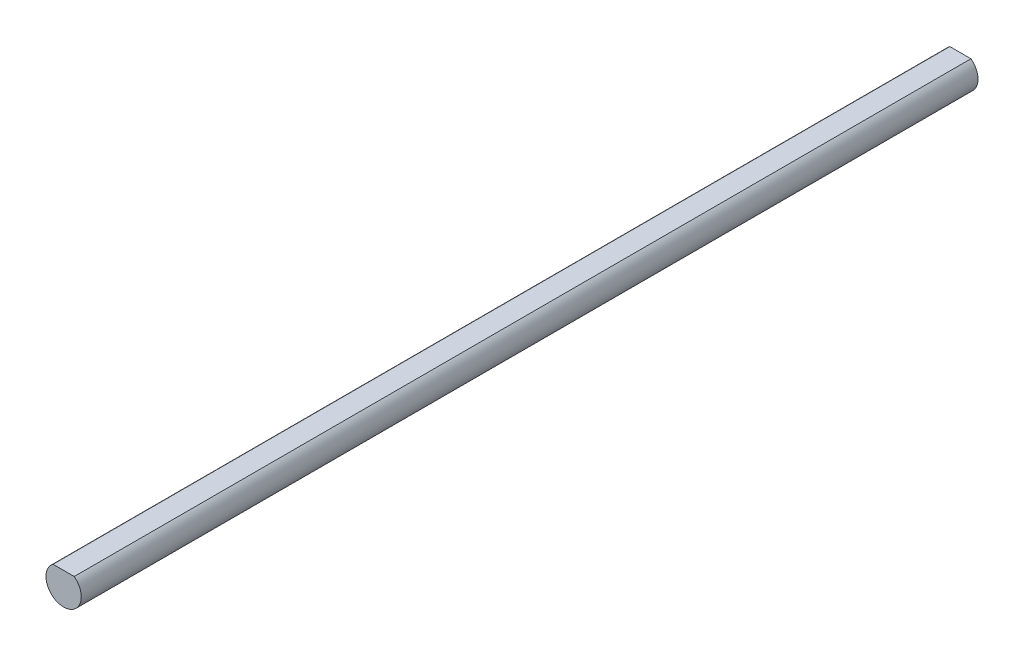
SolidWorks part; units mm, degrees
ref_plane "Front Plane" through (0, 0, 0) normal (0, 0, 1) x (1, 0, 0)
ref_plane "Top Plane" through (0, 0, 0) normal (0, 1, 0) x (1, 0, 0)
ref_plane "Right Plane" through (0, 0, 0) normal (1, 0, 0) x (0, 0, -1)
sketch "Sketch1" plane through (0, 0, 0) normal (0, 0, 1) x (1, 0, 0)
  line L0 (-1.5, 2) -> (1.5, 2)
  arc A0 (-1.5, 2) -> (1.5, 2) centre (0, 0) ccw
  dimension "D1" = 5
  dimension "D2" = 2
extrude "Boss-Extrude1" add sketch "Sketch1" along normal blind 127
